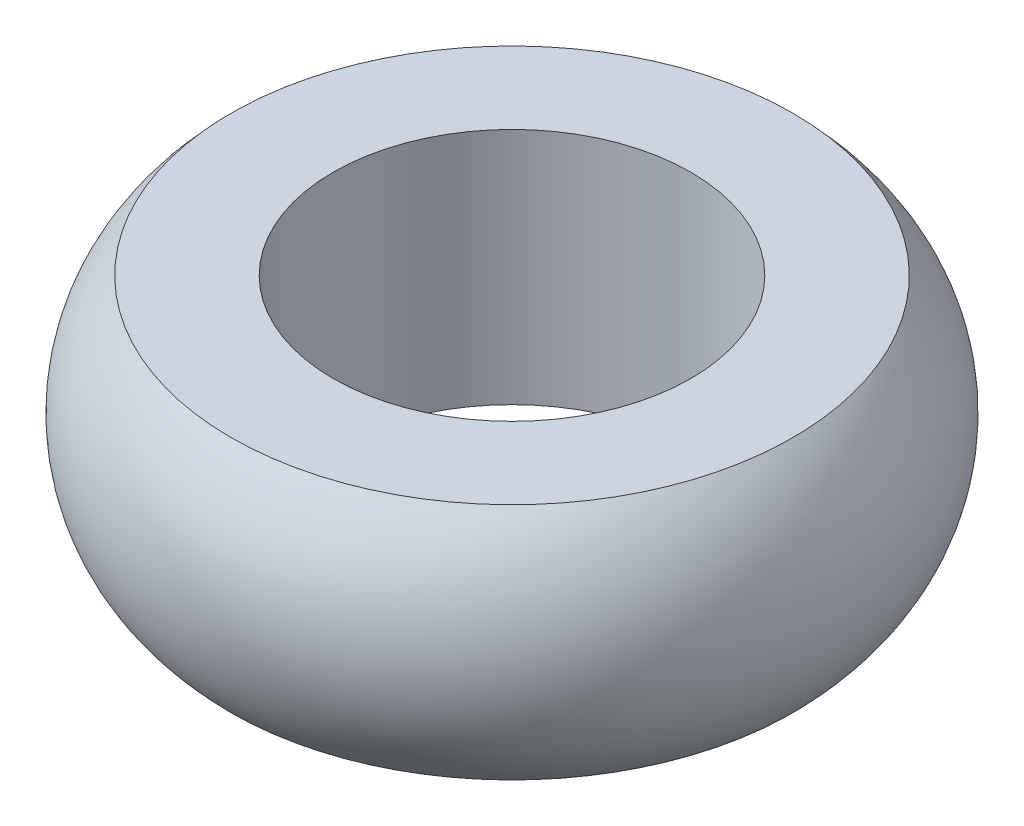
SolidWorks part; units mm, degrees
ref_plane "Płaszczyzna przednia" through (0, 0, 0) normal (0, 0, 1) x (1, 0, 0)
ref_plane "Płaszczyzna górna" through (0, 0, 0) normal (0, 1, 0) x (1, 0, 0)
ref_plane "Płaszczyzna prawa" through (0, 0, 0) normal (1, 0, 0) x (0, 0, -1)
sketch "Sketch1" plane through (0, 0, 0) normal (0, 0, 1) x (1, 0, 0)
  line L0 (0, 0) -> (0, 11.3433) construction
  line L1 (-5.25, 7) -> (-5.25, 0)
  line L2 (-5.25, 0) -> (-8.25, 0)
  line L3 (-5.25, 7) -> (-8.25, 7)
  line L4 (-10, 11.3433) -> (-10, 0) construction
  arc A0 (-8.25, 0) -> (-8.25, 7) centre (-4.6793, 3.5) cw
  dimension "D2" = 10
  dimension "D5" = 5
  dimension "D1" = 5.25
  dimension "D3" = 3
  dimension "D4" = 3
  dimension "D6" = 7
revolve "Revolve1" add sketch "Sketch1" angle 360 about L0
